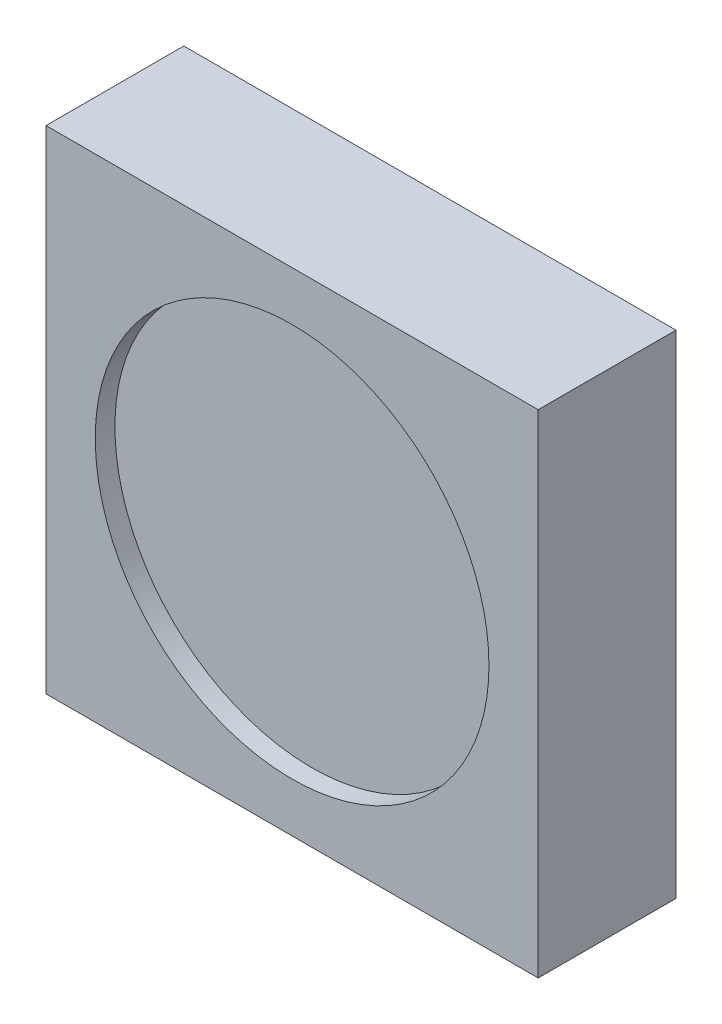
SolidWorks part; units mm, degrees
material "ABS"
ref_plane "Front Plane" through (0, 0, 0) normal (0, 0, 1) x (1, 0, 0)
ref_plane "Top Plane" through (0, 0, 0) normal (0, 1, 0) x (1, 0, 0)
ref_plane "Right Plane" through (0, 0, 0) normal (1, 0, 0) x (0, 0, -1)
sketch "Sketch1" plane through (0, 0, 0) normal (0, 0, 1) x (1, 0, 0)
  line L1 (-2.5, 2.5) -> (2.5, 2.5)
  line L2 (-2.5, 2.5) -> (-2.5, -2.5)
  line L3 (-2.5, -2.5) -> (2.5, -2.5)
  line L4 (2.5, 2.5) -> (2.5, -2.5)
  line L5 (-2.5, 2.5) -> (2.5, -2.5) construction
  line L6 (-2.5, -2.5) -> (2.5, 2.5) construction
  point P0 (0, 0)
  dimension "D1" = 5
  dimension "D2" = 5
extrude "Boss-Extrude1" add sketch "Sketch1" along normal blind 1.4
sketch "Sketch2" plane through (0, 0, 1.4) normal (0, 0, 1) x (1, 0, 0)
  circle A0 centre (0, 0) radius 2
  dimension "D1" = 4
extrude "Cut-Extrude1" cut sketch "Sketch2" against normal blind 0.2
